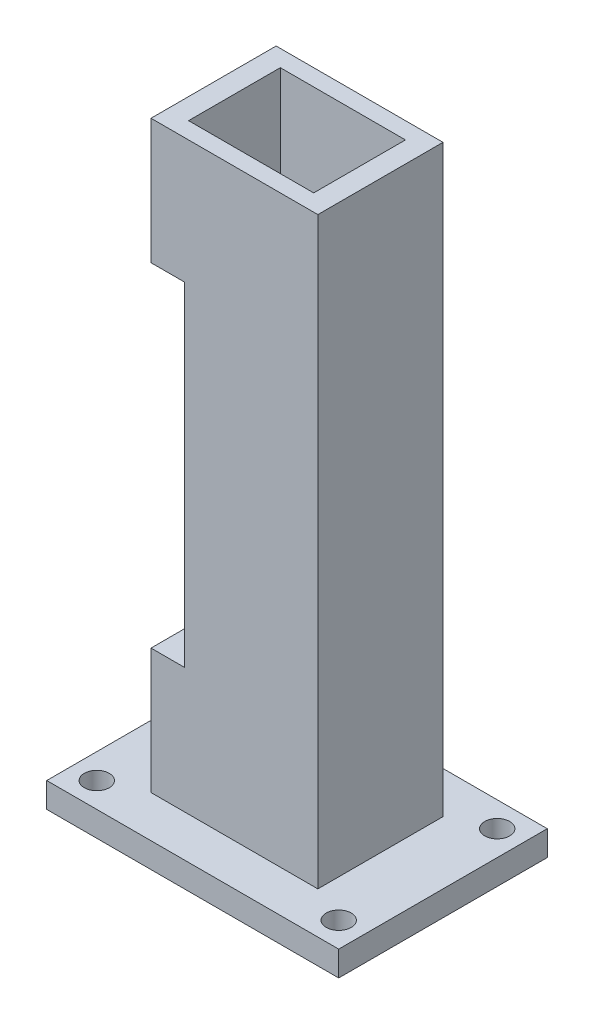
SolidWorks part; units mm, degrees
ref_plane "前视基准面" through (0, 0, 0) normal (0, 0, 1) x (1, 0, 0)
ref_plane "上视基准面" through (0, 0, 0) normal (0, 1, 0) x (1, 0, 0)
ref_plane "右视基准面" through (0, 0, 0) normal (1, 0, 0) x (0, 0, -1)
sketch "草图1" plane through (0, 0, 0) normal (0, 1, 0) x (1, 0, 0)
  line L1 (-17.5, -12.5) -> (17.5, -12.5)
  line L2 (-17.5, -12.5) -> (-17.5, 12.5)
  line L3 (-17.5, 12.5) -> (17.5, 12.5)
  line L4 (17.5, -12.5) -> (17.5, 12.5)
  line L5 (-17.5, -12.5) -> (17.5, 12.5) construction
  line L6 (-17.5, 12.5) -> (17.5, -12.5) construction
  point P0 (0, 0)
  dimension "D1" = 35
  dimension "D2" = 25
extrude "凸台-拉伸1" add sketch "草图1" along normal blind 3
sketch "草图2" plane through (0, 3, 0) normal (0, 1, 0) x (1, 0, 0)
  line L1 (-10, -7.5) -> (10, -7.5)
  line L2 (-10, -7.5) -> (-10, 7.5)
  line L3 (-10, 7.5) -> (10, 7.5)
  line L4 (10, -7.5) -> (10, 7.5)
  line L5 (-10, -7.5) -> (10, 7.5) construction
  line L6 (-10, 7.5) -> (10, -7.5) construction
  point P0 (0, 0)
  dimension "D1" = 20
  dimension "D2" = 15
extrude "凸台-拉伸2" add sketch "草图2" along normal blind 70
sketch "草图3" plane through (0, 73, 0) normal (0, 1, 0) x (1, 0, 0)
  line L1 (-7.5, -5.5) -> (7.5, -5.5)
  line L2 (-7.5, -5.5) -> (-7.5, 5.5)
  line L3 (-7.5, 5.5) -> (7.5, 5.5)
  line L4 (7.5, -5.5) -> (7.5, 5.5)
  line L5 (-7.5, -5.5) -> (7.5, 5.5) construction
  line L6 (-7.5, 5.5) -> (7.5, -5.5) construction
  point P0 (0, 0)
  dimension "D1" = 11
  dimension "D2" = 15
extrude "切除-拉伸1" cut sketch "草图3" against normal up to next
sketch "草图4" plane through (0, 0, 7.5) normal (0, 0, 1) x (1, 0, 0)
  line L0 (-10, 58) -> (-6, 58)
  line L1 (-10, 73) -> (-10, 3) construction
  line L2 (-6, 58) -> (-6, 18)
  line L3 (-6, 18) -> (-10, 18)
  line L5 (-17.5, 3) -> (17.5, 3) construction
  line L6 (-10, 58) -> (-10, 18)
  dimension "D1" = 40
  dimension "D2" = 15
  dimension "D3" = 4
extrude "切除-拉伸2" cut sketch "草图4" against normal up to next
sketch "草图5" plane through (0, 3, 0) normal (0, 1, 0) x (1, 0, 0)
  line L0 (0, 12.5) -> (0, -12.5) construction
  line L1 (17.5, 12.5) -> (-17.5, 12.5) construction
  line L2 (-17.5, -12.5) -> (17.5, -12.5) construction
  line L3 (-17.5, 0) -> (17.5, 0) construction
  line L4 (-17.5, 12.5) -> (-17.5, -12.5) construction
  line L5 (17.5, -12.5) -> (17.5, 12.5) construction
  circle A0 centre (-14.5, 9.5) radius 1.5
  circle A1 centre (14.5, 9.5) radius 1.5
  circle A2 centre (-14.5, -9.5) radius 1.5
  circle A3 centre (14.5, -9.5) radius 1.5
  dimension "D1" = 3
  dimension "D2" = 3
  dimension "D3" = 3
  dimension "D4" = 3
  dimension "D5" = 3
  dimension "D6" = 3
  dimension "D7" = 3
  dimension "D8" = 3
  dimension "D9" = 3
  dimension "D10" = 3
  dimension "D11" = 3
  dimension "D12" = 3
extrude "切除-拉伸3" cut sketch "草图5" against normal up to next
